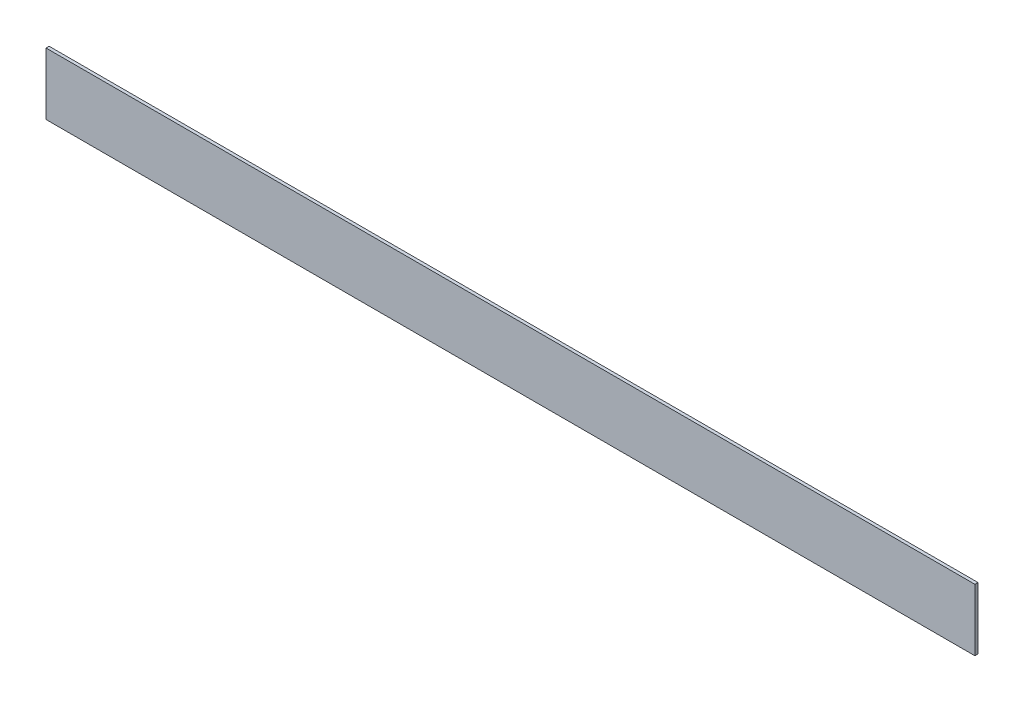
SolidWorks part; units mm, degrees
material "Maple"
ref_plane "Front Plane" through (0, 0, 0) normal (0, 0, 1) x (1, 0, 0)
ref_plane "Top Plane" through (0, 0, 0) normal (0, 1, 0) x (1, 0, 0)
ref_plane "Right Plane" through (0, 0, 0) normal (1, 0, 0) x (0, 0, -1)
sketch "Sketch1" plane through (0, 0, 0) normal (0, 0, 1) x (1, 0, 0)
  line L1 (-1500, 100) -> (1500, 100)
  line L2 (-1500, 100) -> (-1500, -100)
  line L3 (-1500, -100) -> (1500, -100)
  line L4 (1500, 100) -> (1500, -100)
  line L5 (-1500, 100) -> (1500, -100) construction
  line L6 (-1500, -100) -> (1500, 100) construction
  point P0 (0, 0)
  dimension "D1" = 3000
  dimension "D2" = 200
extrude "Boss-Extrude1" add sketch "Sketch1" along normal blind 10
